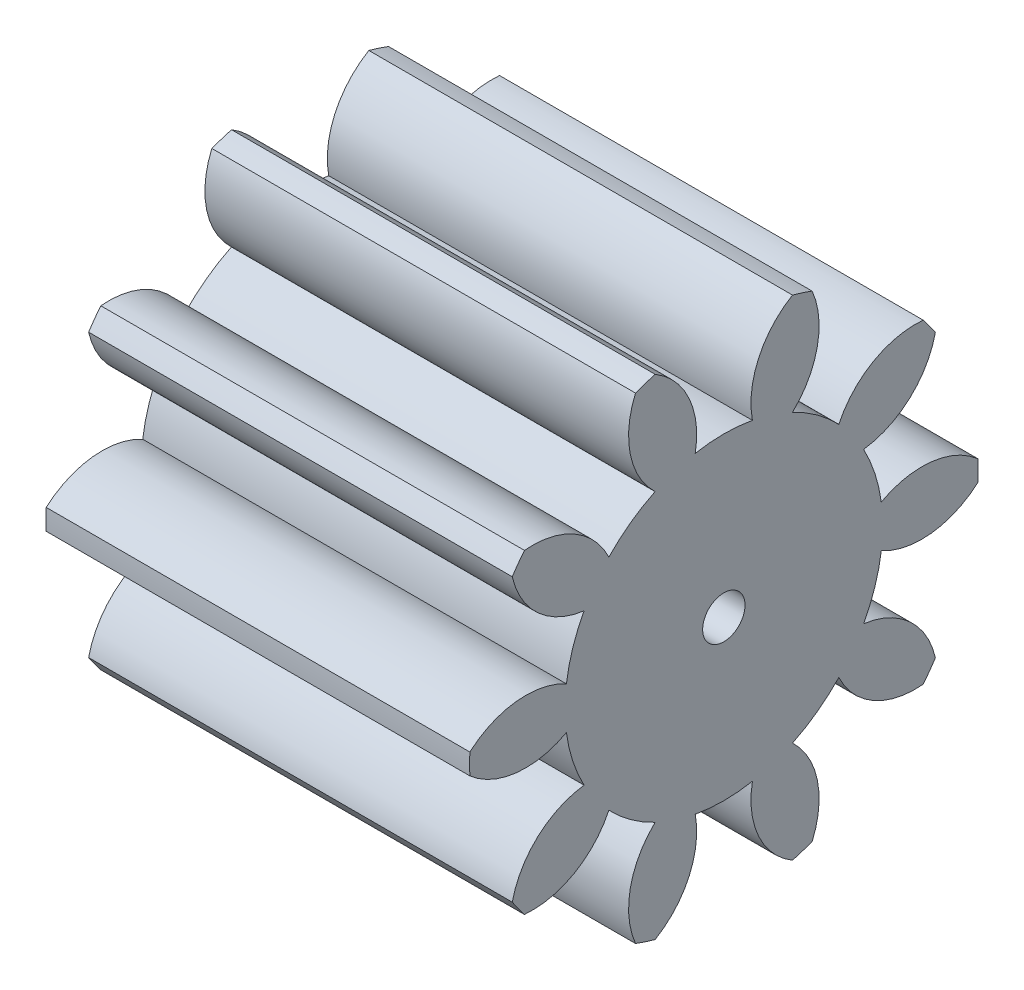
SolidWorks part; units mm, degrees
ref_plane "Plane1" through (0, 0, 0) normal (0, 0, 1) x (1, 0, 0)
ref_plane "Plane2" through (0, 0, 0) normal (0, 1, 0) x (1, 0, 0)
ref_plane "Plane3" through (0, 0, 0) normal (1, 0, 0) x (0, 0, -1)
other "Configuration Table"
sketch "HoldingSke" plane through (0, 0, 0) normal (0, 1, 0) x (1, 0, 0)
  line L0 (0, 0) -> (0.4924, -0.0868)
  line L1 (-15, 0) -> (100, 0) construction
  line L2 (0, 0) -> (-2.1039, 2.3779)
  line L3 (0, 0) -> (-11.863, 4.5341)
  line L4 (0, 0) -> (8.5048, 1.4996)
  line L5 (0, 0) -> (-46.8476, -17.4728)
  line L6 (0, 0) -> (-16.5793, -11.1861)
  line L7 (-2.1039, 2.3779) -> (8.6586, 51.2059)
  line L8 (-76.2, 54.61) -> (-75.9, 54.61)
  line L9 (-67.7845, 28.3722) -> (-49.3413, 33.142)
  line L10 (-76.2, 71.12) -> (104.1128, 71.12)
  line L11 (0, 0) -> (-20, 0)
  line L12 (-76.2, 101.6) -> (-76.133, 101.6)
  line L13 (24.9733, 27.94) -> (52.9518, 28.4284)
  line L14 (24.9733, 27.94) -> (24.9743, 27.94)
  line L15 (24.9733, 27.94) -> (100.4006, 29.5858)
  line L16 (-63.627, -2) -> (-12.827, -2)
  circle A0 centre (0, 0) radius 1
  circle A1 centre (0, 0) radius 7.499
  circle A2 centre (0, 0) radius 37.5
  circle A3 centre (0, 0) radius 1
  dimension "MHD" = 14.998
  dimension "Hub_dia" = 75
  dimension "Bore" = 2
  dimension "MBD" = 2
  dimension "Num_teeth" = 10
  dimension "Pitch" = 0.5
  dimension "Overall_len" = 50
  dimension "Show_teeth" = 10
  dimension "Thickness" = 20
  dimension "OAL" = 50.0001
  dimension "T_dim" = 0.3
  dimension "Ap" = 14.5
  dimension "H" = 19.05
  dimension "Pitch_radius" = 180.3128
  dimension "Width" = 20
  dimension "Backlash" = 0.067
  dimension "Addendum_fac" = 1
  dimension "Dedendum_fac" = 1.25
  dimension "Clearance_fac" = 0.25
  dimension "Dedendum_add" = 0.001
  dimension "Module" = 2
sketch "BasProSke" plane through (0, 0, 0) normal (0, 1, 0) x (1, 0, 0)
  line L0 (-10, 0) -> (60, 0) construction
  line L1 (0, 0) -> (0, 12)
  line L2 (0, 0) -> (20, 0)
  line L3 (20, 0) -> (20, 12)
  line L4 (20, 12) -> (0, 12)
  dimension "Thickness" = 20
  dimension "Diameter" = 24
revolve "Base-Revolve" add sketch "BasProSke" angle 360 about L0
sketch "TooCutSke" plane through (0, 0, 0) normal (1, 0, 0) x (0, 0, -1)
  line L1 (0, 0) -> (0, 107) construction
  line L2 (0, 0) -> (-1.6814, 9.8576) construction
  line L3 (0, 0) -> (-6.1153, 18.8209) construction
  line L4 (-1.6814, 9.8576) -> (-3.0576, 9.4105) construction
  arc A0 (1.35, 7.3765) -> (-1.35, 7.3765) centre (0, 0) ccw
  arc A1 (3.2708, 11.572) -> (-3.2708, 11.572) centre (0, 0) ccw
  circle A2 centre (0, 0) radius 10 construction
  circle A3 centre (0, 0) radius 9.6815 construction
  arc A4 (-1.35, 7.3765) -> (-3.2708, 11.572) centre (-5.2814, 8.1141) ccw
  arc A5 (3.2708, 11.572) -> (1.35, 7.3765) centre (5.2814, 8.1141) ccw
  dimension "Root_dia" = 14.998
  dimension "Overcut_dia" = 24.0508
  dimension "Pitch_dia" = 20
  dimension "Base_dia" = 19.363
  dimension "Flank_rad" = 4
  dimension "Half_ang" = 18
  dimension "Half_CT" = 1.4471
extrude "ToothCut" cut sketch "TooCutSke" along normal through all
fillet "Breaks" [suppressed] radius 0.04
fillet "RootFillets" [suppressed] radius 0.501
pattern_circular "TeethCuts" count 10 every 36 about axis through (-10, 0, 0) along (1, 0, 0) of "ToothCut", "RootFillets", "Breaks"
sketch "HubNeaOneSke" plane through (0, 0, 0) normal (-1, 0, 0) x (0, 0, 1)
  circle A0 centre (0, 0) radius 7.499
  dimension "Diameter" = 14.998
extrude "HubNearOne" [suppressed] add sketch "HubNeaOneSke" along normal blind 30.0001
sketch "HubNeaBotSke" plane through (0, 0, 0) normal (-1, 0, 0) x (0, 0, 1)
  circle A0 centre (0, 0) radius 7.499
  dimension "Diameter" = 14.998
extrude "HubNearBoth" [suppressed] add sketch "HubNeaBotSke" along normal blind 15.0001
ref_plane "FarPln" through (20, 0, 0) normal (1, 0, 0) x (0, 0, -1)
sketch "HubFarSke" plane through (20, 0, 0) normal (1, 0, 0) x (0, 0, -1)
  circle A0 centre (0, 0) radius 7.499
  dimension "Diameter" = 14.998
extrude "HubFar" [suppressed] add sketch "HubFarSke" along normal blind 15.0001
sketch "BorSke" plane through (0, 0, 0) normal (1, 0, 0) x (0, 0, -1)
  circle A0 centre (0, 0) radius 1
  dimension "Diameter" = 2
extrude "Bore" cut sketch "BorSke" along normal mid plane 100.0002
sketch "KeySke" plane through (0, 0, 0) normal (1, 0, 0) x (0, 0, -1)
  line L0 (-0.4, 0) -> (-0.4, 1.3)
  line L1 (-0.4, 1.3) -> (0.4, 1.3)
  line L2 (0.4, 1.3) -> (0.4, 0)
  line L3 (0, 0) -> (0, 34) construction
  line L4 (-0.4, 0) -> (0.4, 0)
  dimension "Offset" = 1.3
  dimension "Width" = 0.8
extrude "Keyway" [suppressed] cut sketch "KeySke" along normal mid plane 100.0002
pattern_circular "Keyway2" [suppressed] count 2 every 90 about axis through (-10, 0, 0) along (1, 0, 0)
equation "' \"Module@HoldingSke\" = 6.35"
equation "' \"Num_teeth@HoldingSke\" = 12"
equation "' \"Ap@HoldingSke\" =  20"
equation "' \"Ap@HoldingSke\" = 20"
equation "' \"Width@HoldingSke\" = 0.5 * 25.4"
equation "' \"Hub_dia@HoldingSke\"= 1 * 25.4"
equation "' \"Hub_dia@HoldingSke\" = 1 * 25.4"
equation "' \"Overall_len@HoldingSke\" = 1.0 * 25.4"
equation "' \"Bore@HoldingSke\" = 0.75 * 25.4"
equation "' \"T_dim@HoldingSke\" = 0.1 * 25.4"
equation "' \"Width@KeySke\" = 0.25 * 25.4"
equation "' \"Show_teeth@HoldingSke\" = 13"
equation "' \"Backlash@HoldingSke\" = 0.009 * 25.4"
equation "' \"Addendum_fac@HoldingSke\" = 1.0"
equation "' \"Dedendum_fac@HoldingSke\" = 1.25"
equation "' \"Dedendum_add@HoldingSke\" = 0.00005 * 25.4"
equation "' \"Clearance_fac@HoldingSke\" = 0.25"
equation "\"Pitch@HoldingSke\" = 1 / \"Module@HoldingSke\""
equation "\"Overcut_dia@TooCutSke\" = (\"Num_teeth@HoldingSke\" + 2 * \"Addendum_fac@HoldingSke\") / \"Pitch@HoldingSke\" + 0.002 * 25.4"
equation "\"Pitch_dia@TooCutSke\" = \"Num_teeth@HoldingSke\" / \"Pitch@HoldingSke\""
equation "\"Base_dia@TooCutSke\" = \"Num_teeth@HoldingSke\" / \"Pitch@HoldingSke\" * cos((\"Ap@HoldingSke\"  * 3.14159265 / 180))"
equation "\"Root_dia@TooCutSke\" = (\"Num_teeth@HoldingSke\" + 2) / \"Pitch@HoldingSke\" - 2 * (\"Addendum_fac@HoldingSke\" + \"Dedendum_fac@HoldingSke\") / \"Pitch@HoldingSke\" - \"Dedendum_add@HoldingSke\" * 2"
equation "\"Half_ang@TooCutSke\" = 180 / \"Num_teeth@HoldingSke\""
equation "\"Half_CT@TooCutSke\" = \"Num_teeth@HoldingSke\" / \"Pitch@HoldingSke\" * sin((3.14159265 / 2 / \"Num_teeth@HoldingSke\")) / 2 - 7 * \"Backlash@HoldingSke\" / 4"
equation "\"Flank_rad@TooCutSke\" = \"Num_teeth@HoldingSke\" / \"Pitch@HoldingSke\" / 5"
equation "\"Radius@RootFillets\" = \"Clearance_fac@HoldingSke\" / \"Pitch@HoldingSke\" + \"Dedendum_add@HoldingSke\""
equation "\"Break_rad@Breaks\" = 0.02 / \"Pitch@HoldingSke\""
equation "\"Thickness@HoldingSke\" = \"Width@HoldingSke\""
equation "\"OAL@HoldingSke\" = \"Thickness@HoldingSke\""
equation "\"MHD@HoldingSke\" = (\"Num_teeth@HoldingSke\" + 2) / \"Pitch@HoldingSke\" - 2 * (\"Addendum_fac@HoldingSke\" + \"Dedendum_fac@HoldingSke\")  / \"Pitch@HoldingSke\" - \"Dedendum_add@HoldingSke\" * 2"
equation "\"MBD@HoldingSke\" = (\"Num_teeth@HoldingSke\" + 2) / \"Pitch@HoldingSke\" - 2 * (\"Addendum_fac@HoldingSke\" + \"Dedendum_fac@HoldingSke\")  / \"Pitch@HoldingSke\" - \"Dedendum_add@HoldingSke\" * 2 - 0.002 * 25.4"
equation "\"MHD@HoldingSke\" = ((sgn( \"MHD@HoldingSke\" - \"Hub_dia@HoldingSke\" )-1)*( \"MHD@HoldingSke\" - \"Hub_dia@HoldingSke\" ))/-2+ \"Hub_dia@HoldingSke\""
equation "\"MBD@HoldingSke\" = ((sgn( \"MBD@HoldingSke\" - \"Bore@HoldingSke\" )-1)*( \"MBD@HoldingSke\" - \"Bore@HoldingSke\" ))/-2+ \"Bore@HoldingSke\""
equation "\"OAL@HoldingSke\" = ((sgn( \"OAL@HoldingSke\" - \"Overall_len@HoldingSke\" )+1)*( \"OAL@HoldingSke\" - \"Overall_len@HoldingSke\" ))/2 + \"Overall_len@HoldingSke\" + 0.000002 * 25.4"
equation "\"Num_teeth@TeethCuts\" = int( \"Show_teeth@HoldingSke\" ) + 1"
equation "\"Num_teeth@TeethCuts\" = ((sgn( \"Num_teeth@TeethCuts\" - \"Num_teeth@HoldingSke\" )-1)*( \"Num_teeth@TeethCuts\" - \"Num_teeth@HoldingSke\" ))/-2+ \"Num_teeth@HoldingSke\""
equation "\"Num_teeth@TeethCuts\" = ((sgn( \"Num_teeth@TeethCuts\" - 2.0)+1)*( \"Num_teeth@TeethCuts\" - 2.0))/2 +2.0"
equation "\"Angle@TeethCuts\" = 360.0 / \"Num_teeth@HoldingSke\""
equation "\"Diameter@BasProSke\" = (\"Num_teeth@HoldingSke\" + 2 * \"Addendum_fac@HoldingSke\") / \"Pitch@HoldingSke\""
equation "\"Thickness@BasProSke\"  = \"Thickness@HoldingSke\""
equation "' \"Fillet_rad@BasProSke\" =  \"Thickness@HoldingSke\" * 0.05"
equation "' \"Fillet_rad@BasProSke\" = \"Thickness@HoldingSke\" * 0.05"
equation "\"MHD@HoldingSke\" = ((sgn( \"MHD@HoldingSke\" - \"Root_dia@TooCutSke\" )-1)*( \"MHD@HoldingSke\" - \"Root_dia@TooCutSke\" ))/-2+ \"Root_dia@TooCutSke\""
equation "\"Diameter@HubNeaOneSke\" = \"MHD@HoldingSke\""
equation "\"Length@HubNearOne\" = \"OAL@HoldingSke\" - \"Thickness@BasProSke\""
equation "\"Diameter@HubNeaBotSke\" = \"MHD@HoldingSke\""
equation "\"Length@HubNearBoth\" = ( \"OAL@HoldingSke\" - \"Thickness@BasProSke\" ) / 2.0"
equation "\"Thickness@FarPln\" = \"Thickness@BasProSke\""
equation "\"Diameter@HubFarSke\" = \"MHD@HoldingSke\""
equation "\"Length@HubFar\" = ( \"OAL@HoldingSke\" - \"Thickness@BasProSke\" ) / 2.0"
equation "\"Diameter@BorSke\" = \"MBD@HoldingSke\""
equation "\"D1@Bore\" = \"OAL@HoldingSke\" * 2.0"
equation "\"D1@Keyway\" = \"OAL@HoldingSke\" * 2.0"
equation "\"Offset@KeySke\" = \"T_dim@HoldingSke\" + \"MBD@HoldingSke\" / 2.0"
